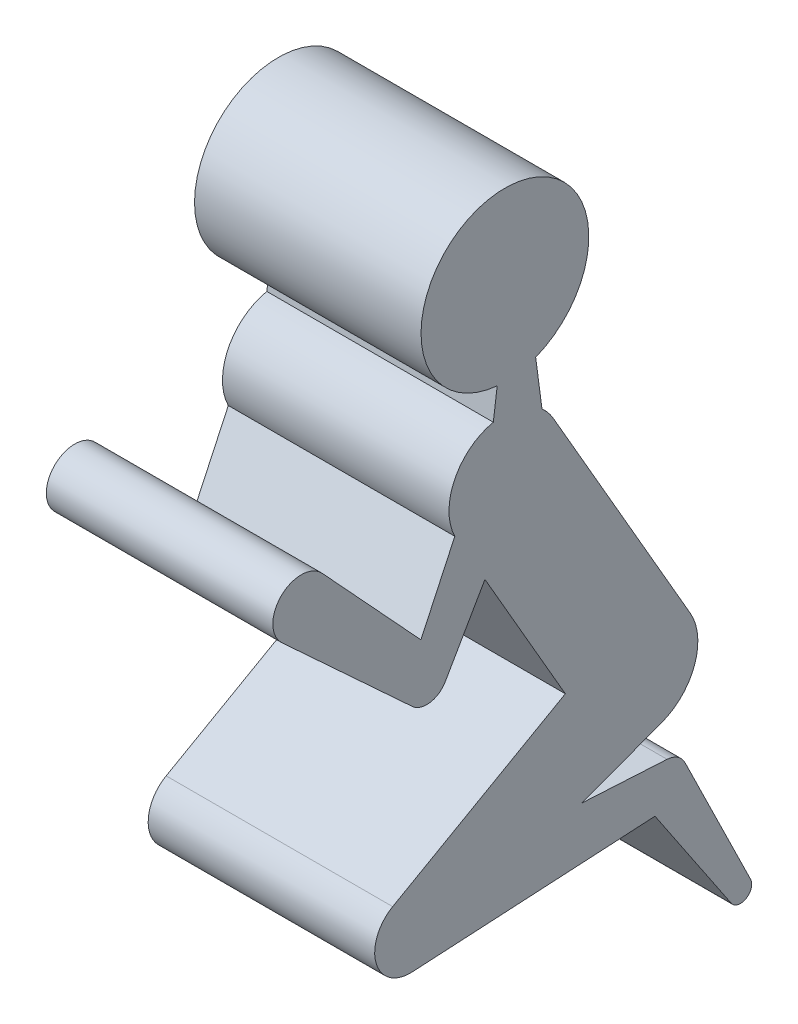
SolidWorks part; units mm, degrees
ref_plane "Front Plane" through (0, 0, 0) normal (0, 0, 1) x (1, 0, 0)
ref_plane "Top Plane" through (0, 0, 0) normal (0, 1, 0) x (1, 0, 0)
ref_plane "Right Plane" through (0, 0, 0) normal (1, 0, 0) x (0, 0, -1)
sketch "Sketch1" plane through (0, 0, 0) normal (1, 0, 0) x (0, 0, -1)
  line L0 (457.2, 0) -> (0, 0) construction
  line L1 (0, 0) -> (414.3639, 193.2211) construction
  line L2 (414.3639, 193.2211) -> (169.3809, 617.5441) construction
  line L3 (169.3809, 617.5441) -> (29.6809, 375.5766) construction
  line L4 (29.6809, 375.5766) -> (-194.8255, 600.083) construction
  line L5 (-457.2, 0) -> (-853.1468, -228.6) construction
  line L6 (0, 0) -> (-457.2, 0) construction
  line L7 (0, 0) -> (126.8125, 473.2708) construction
  line L8 (126.8125, 473.2708) -> (-117.9743, 338.572) construction
  line L9 (-117.9743, 338.572) -> (-414.0325, 453.2708) construction
  line L10 (169.3809, 617.5441) -> (169.3809, 917.5441) construction
  line L12 (169.3809, 717.5441) -> (169.3809, 767.5441) construction
  line L13 (457.2, 0) -> (590.55, -230.969) construction
  line L14 (-853.1468, -228.6) -> (-965.8591, 13.1123) construction
  circle A0 centre (0, 0) radius 63.5
  circle A1 centre (414.3639, 193.2211) radius 100
  circle A2 centre (-194.8255, 600.083) radius 50.8
  circle A3 centre (29.6809, 375.5766) radius 38.1
  circle A4 centre (169.3809, 617.5441) radius 100
  circle A5 centre (169.3809, 917.5441) radius 150
  circle A6 centre (457.2, 0) radius 38.1
  arc A7 (-393.8006, 499.8681) -> (-430.4748, 405.2053) centre (-414.0325, 453.2708) ccw construction
  arc A8 (-130.3061, 302.5229) -> (-107.458, 301.9522) centre (-117.9743, 338.572) ccw construction
  circle A9 centre (126.8125, 473.2708) radius 100 construction
  circle A10 centre (142.3511, 759.5435) radius 150 construction
  circle A11 centre (0, 0) radius 100 construction
  circle A12 centre (-457.2, 0) radius 63.5 construction
  circle A13 centre (-853.1468, -228.6) radius 38.1 construction
  dimension "D1" = 50
  dimension "D2" = 25
  dimension "D3" = 150
  dimension "D4" = 85
  dimension "D5" = 60
  dimension "D6" = 75
  dimension "D7" = 120
sketch "Sketch2" plane through (0, 0, 0) normal (1, 0, 0) x (0, 0, -1)
  line L0 (500.9665, 243.2211) -> (255.9835, 667.5441)
  line L1 (169.3809, 617.5441) -> (169.3809, 917.5441) construction
  line L2 (224.3809, 777.9912) -> (235.6441, 692.4386)
  line L3 (155.5665, 768.1816) -> (148.6129, 715.3638)
  line L4 (79.7737, 573.1532) -> (-4.8494, 391.6783)
  line L5 (156.1477, 518.4235) -> (62.6765, 356.5266)
  line L6 (169.3809, 617.5441) -> (29.6809, 375.5766) construction
  line L7 (-157.4964, 634.5384) -> (57.6778, 401.4182)
  line L8 (327.7614, 143.2211) -> (82.7784, 567.5441)
  line L9 (-229.2809, 562.7539) -> (3.8393, 347.5797)
  line L10 (414.3639, 193.2211) -> (169.3809, 617.5441) construction
  line L11 (-31.3451, 55.2244) -> (365.0016, 280.1887)
  line L12 (22.1561, -59.5093) -> (449.2555, 99.5056)
  line L13 (459.3167, 38.0412) -> (3.5278, 63.4019)
  line L14 (3.5278, -63.4019) -> (459.3167, -38.0412)
  line L15 (491.4124, 16.7668) -> (608.5092, -222.1675)
  line L17 (425.5734, -21.2454) -> (573.9481, -242.1214)
  circle A0 centre (169.3809, 917.5441) radius 150
  circle A1 centre (169.3809, 617.5441) radius 100
  circle A2 centre (29.6809, 375.5766) radius 38.1
  circle A3 centre (414.3639, 193.2211) radius 100
  circle A4 centre (457.2, 0) radius 38.1
  circle A5 centre (0, 0) radius 63.5
  circle A6 centre (-194.8255, 600.083) radius 50.8
  circle A7 centre (-194.8255, 600.083) radius 50.8 construction
  circle A8 centre (169.3809, 917.5441) radius 150 construction
  circle A9 centre (169.3809, 617.5441) radius 100 construction
  circle A10 centre (29.6809, 375.5766) radius 38.1 construction
  circle A11 centre (414.3639, 193.2211) radius 100 construction
  circle A12 centre (0, 0) radius 63.5 construction
  circle A13 centre (457.2, 0) radius 38.1 construction
  circle A14 centre (590.55, -230.969) radius 20
  dimension "D1" = 7.5
  dimension "D6" = 40
  dimension "D2" = 7.5
  dimension "D3" = 90
  dimension "D4" = 55
  dimension "D5" = 5
extrude "Boss-Extrude1" add sketch "Sketch2" along normal mid plane 405 contours A0 | A1 L2 A0 L3 | A1 | A1 L8 L5 | A2 L5 L8 A1 L4 L7 | A2 | A2 L7 L4 | A6 L9 A2 L4 L7 | A6 | A3 L0 A1 L5 L8 L11 | A3 L11 L8 | A3 | A5 L13 L12 A3 L8 L11 | A5 | A5 L12 L13 | A5 L14 L17 A4 L13 L12 | A4 | A14 L15 A4 L14 L17 | A14 | A4 L17 L14
